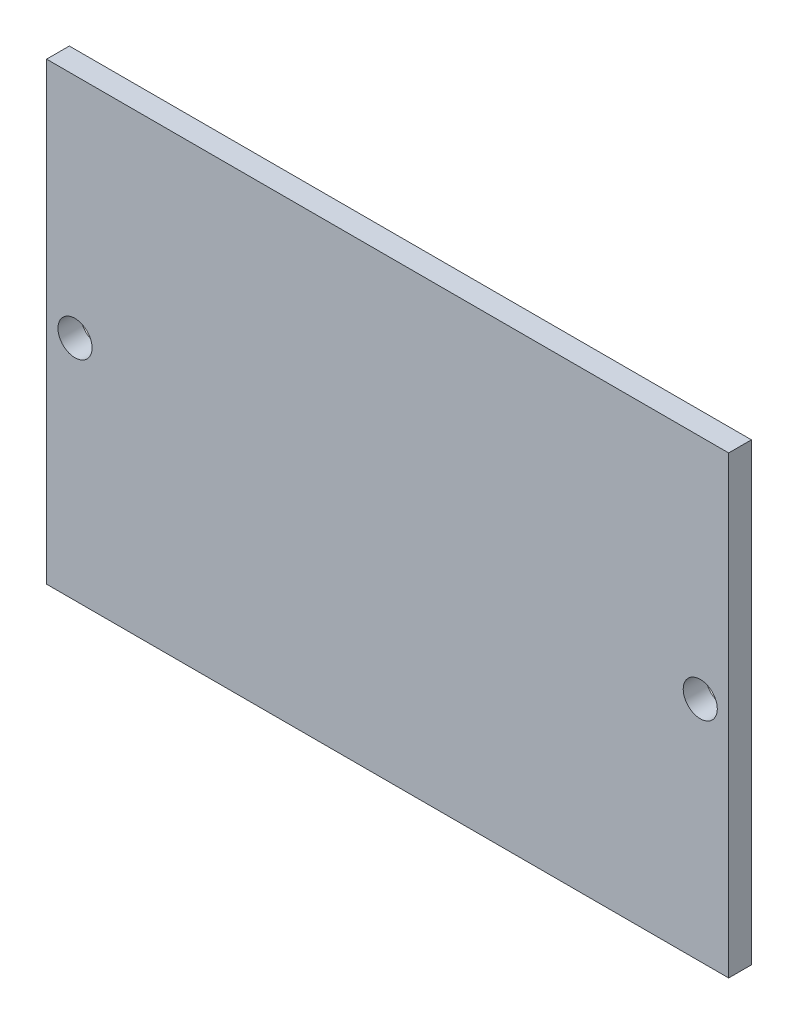
SolidWorks part; units mm, degrees
ref_plane "Front Plane" through (0, 0, 0) normal (0, 0, 1) x (1, 0, 0)
ref_plane "Top Plane" through (0, 0, 0) normal (0, 1, 0) x (1, 0, 0)
ref_plane "Right Plane" through (0, 0, 0) normal (1, 0, 0) x (0, 0, -1)
sketch "Sketch1" plane through (0, 0, 0) normal (0, 0, 1) x (1, 0, 0)
  line L1 (-30, 20) -> (30, 20)
  line L2 (-30, 20) -> (-30, -20)
  line L3 (-30, -20) -> (30, -20)
  line L4 (30, 20) -> (30, -20)
  line L5 (-30, 20) -> (30, -20) construction
  line L6 (-30, -20) -> (30, 20) construction
  point P0 (0, 0)
  dimension "D1" = 60
  dimension "D2" = 40
extrude "Boss-Extrude1" add sketch "Sketch1" along normal blind 2
sketch "Sketch2" plane through (0, 0, 0) normal (0, 0, -1) x (-1, 0, 0)
  line L0 (30, 20) -> (30, -20) construction
  line L1 (-30, -20) -> (-30, 20) construction
  line L2 (-30, 20) -> (30, 20) construction
  circle A0 centre (27.5, 0) radius 1.5
  circle A1 centre (-27.5, 0) radius 1.5
  dimension "D1" = 3
  dimension "D2" = 3
  dimension "D3" = 2.5
  dimension "D4" = 2.5
  dimension "D5" = 20
  dimension "D6" = 20
extrude "Cut-Extrude1" cut sketch "Sketch2" against normal up to next
